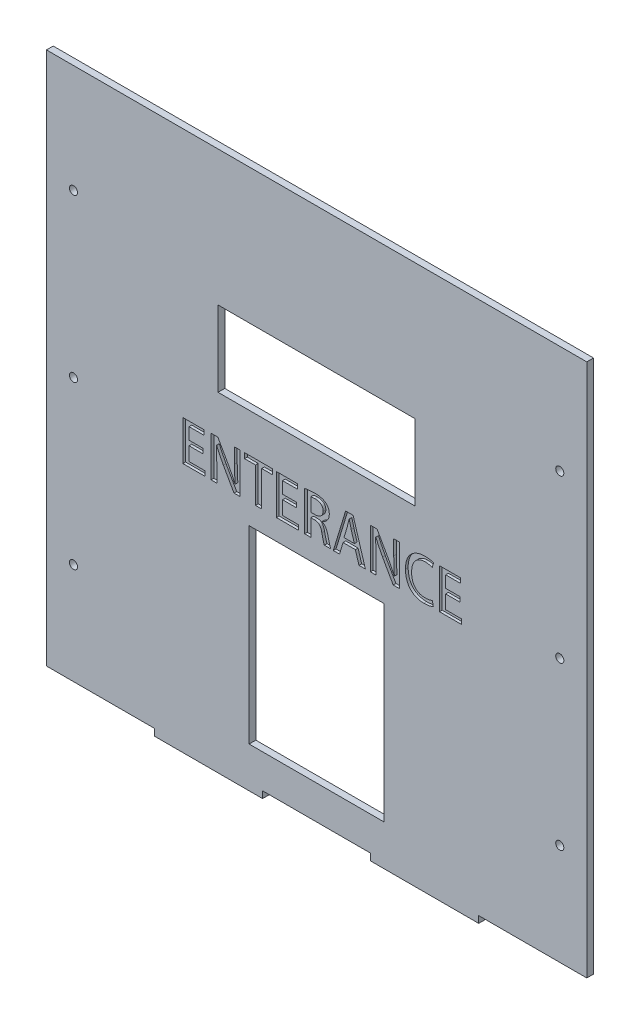
SolidWorks part; units mm, degrees
material "Oak"
ref_plane "Front Plane" through (0, 0, 0) normal (0, 0, 1) x (1, 0, 0)
ref_plane "Top Plane" through (0, 0, 0) normal (0, 1, 0) x (1, 0, 0)
ref_plane "Right Plane" through (0, 0, 0) normal (1, 0, 0) x (0, 0, -1)
sketch "Sketch1" plane through (0, 0, 0) normal (0, 0, 1) x (1, 0, 0)
  line L0 (0, 0) -> (-100, 0) construction
  line L1 (-100, 100) -> (100, 100)
  line L2 (-100, 100) -> (-100, -100)
  line L3 (-100, -100) -> (100, -100)
  line L4 (100, 100) -> (100, -100)
  line L5 (-100, 100) -> (100, -100) construction
  line L6 (-100, -100) -> (100, 100) construction
  line L7 (-20, -100) -> (-20, -97.5)
  line L8 (-100, -100) -> (-60, -100)
  line L9 (-100, -100) -> (-100, -97.5)
  line L10 (-100, -97.5) -> (-60, -97.5)
  line L11 (-60, -100) -> (-60, -97.5)
  line L12 (-20, -100) -> (20, -100)
  line L13 (20, -100) -> (20, -97.5)
  line L14 (-20, -97.5) -> (20, -97.5)
  line L15 (60, -100) -> (60, -97.5)
  line L16 (60, -100) -> (100, -100)
  line L17 (100, -100) -> (100, -97.5)
  line L18 (60, -97.5) -> (100, -97.5)
  line L20 (-25, -85) -> (25, -85)
  line L21 (-25, -85) -> (-25, -15)
  line L22 (-25, -15) -> (25, -15)
  line L23 (25, -85) -> (25, -15)
  line L24 (-25, -85) -> (25, -15) construction
  line L25 (-25, -15) -> (25, -85) construction
  line L26 (-36.5, 50) -> (36.5, 50)
  line L27 (-36.5, 50) -> (-36.5, 22)
  line L28 (-36.5, 22) -> (36.5, 22)
  line L29 (36.5, 50) -> (36.5, 22)
  line L30 (-36.5, 50) -> (36.5, 22) construction
  line L31 (-36.5, 22) -> (36.5, 50) construction
  circle A0 centre (-90, 0) radius 1.5
  circle A1 centre (90, 0) radius 1.5
  circle A2 centre (90, 60) radius 1.5
  circle A3 centre (-90, 60) radius 1.5
  circle A4 centre (90, 0) radius 1.5
  circle A5 centre (90, -60) radius 1.5
  circle A6 centre (-90, -60) radius 1.5
  point P0 (0, 0)
  point P26 (0, -50)
  point P39 (0, -100)
  point P41 (0, 36)
  dimension "D3" = 3
  dimension "D4" = 10
  dimension "D1" = 200
  dimension "D2" = 200
  dimension "D9" = 40
  dimension "D10" = 2.5
  dimension "D12" = 70
  dimension "D13" = 50
  dimension "D14" = 15
  dimension "D15" = 73
  dimension "D16" = 28
  dimension "D17" = 50
  dimension "D5" = 2
  dimension "D6" = 2
  dimension "D7" = 2
  dimension "D8" = 2
  dimension "D11" = 3
extrude "Boss-Extrude1" add sketch "Sketch1" along normal blind 2.5 contours L15 L18 L4 L1 L2 L10 L11 L3 L7 L14 L13 A6 A5 A3 A2 A1 A0 L23 L20 L21 L22 L26 L29 L28 L27
sketch "Sketch2" plane through (0, 0, 2.5) normal (0, 0, 1) x (1, 0, 0)
  text T0 "ENTERANCE" font "@Adobe Fan Heiti Std B" height in points 48
extrude "Cut-Extrude1" cut sketch "Sketch2" against normal blind 1
